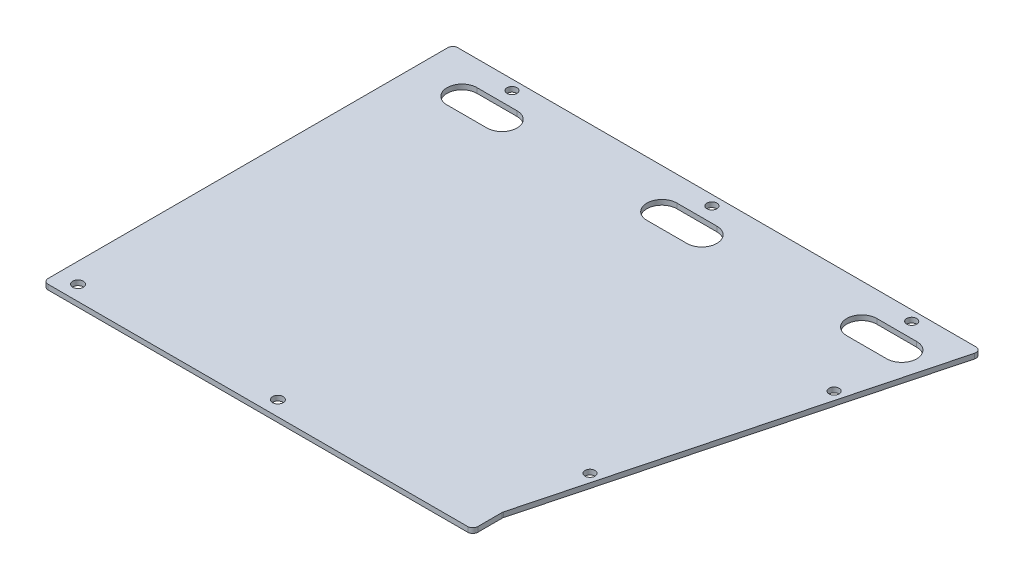
SolidWorks part; units mm, degrees
material "PC High Viscosity"
ref_plane "Front Plane" through (0, 0, 0) normal (0, 0, 1) x (1, 0, 0)
ref_plane "Top Plane" through (0, 0, 0) normal (0, 1, 0) x (1, 0, 0)
ref_plane "Right Plane" through (0, 0, 0) normal (1, 0, 0) x (0, 0, -1)
sketch "Sketch1" plane through (0, 0, 0) normal (0, 1, 0) x (1, 0, 0)
  line L0 (0, 0) -> (273.05, 0)
  line L1 (273.05, 0) -> (273.05, 19.05)
  line L2 (273.05, 19.05) -> (336.55, 260.35)
  line L3 (336.55, 260.35) -> (0, 260.35)
  line L4 (0, 260.35) -> (0, 0)
  dimension "D1" = 260.35
  dimension "D2" = 241.3
  dimension "D3" = 273.05
  dimension "D4" = 336.55
extrude "Boss-Extrude1" add sketch "Sketch1" along normal blind 3.175
fillet "Fillet1" radius 3.175 5 edges at (336.55, 1.5875, -260.35) (0, 1.5875, -260.35) (0, 1.5875, 0) (273.05, 1.5875, 0) (273.05, 1.5875, -19.05)
sketch "Sketch2" plane through (0, 3.175, 0) normal (0, 1, 0) x (1, 0, 0)
  line L0 (311.7215, 190.9534) -> (279.4009, 68.1349) construction
  line L1 (43.9782, 254) -> (297.9782, 254) construction
  line L2 (273.1545, 19.4472) -> (335.5018, 256.367) construction
  line L4 (298.1873, 139.5231) -> (304.3282, 137.9071) construction
  line L5 (332.4314, 260.35) -> (3.175, 260.35) construction
  point P0 (43.9782, 254)
  point P1 (170.9782, 254)
  point P2 (297.9782, 254)
  point P3 (279.4009, 68.1349)
  point P5 (311.7215, 190.9534)
  point P10 (167.8032, 260.35)
  point P15 (304.3282, 137.9071)
  dimension "D1" = 6.35
  dimension "D2" = 6.35
  dimension "D3" = 127
  dimension "D4" = 254
  dimension "D5" = 3.175
  dimension "D6" = 53.1812
hole_wizard "1/4 (0.25) Diameter Hole1" positions "Sketch3" profile "Sketch4" hole size "1/4" standard "ANSI Inch" end condition through all
sketch "Sketch3" plane through (0, 3.175, 0) normal (0, 1, 0) x (1, 0, 0)
  line L0 (43.9782, 254) -> (297.9782, 254) construction
  point P0 (43.9782, 254)
  point P3 (170.9782, 254)
  point P7 (297.9782, 254)
  point P10 (311.7215, 190.9534)
  point P17 (279.4009, 68.1349)
sketch "Sketch4" plane through (43.9782, 3.175, -254) normal (1, 0, 0) x (0, 0, 1)
  line L0 (0, 0) -> (0, 3.175)
  line L1 (0, 3.175) -> (3.175, 3.175)
  line L2 (3.175, 3.175) -> (3.175, 0)
  line L5 (3.175, 0) -> (0, 0)
  line L11 (0, -6.35) -> (0, 107.95) construction
  dimension "Thru Hole Dia." = 6.35
  dimension "Thru Hole Depth" = 3.175
sketch "Sketch5" plane through (0, 3.175, 0) normal (0, 1, 0) x (1, 0, 0)
  line L0 (0, 257.175) -> (0, 3.175) construction
  line L1 (3.175, 0) -> (269.875, 0) construction
  point P0 (12.7, 9.525)
  point P1 (139.7, 9.525)
  dimension "D1" = 127
  dimension "D2" = 12.7
  dimension "D3" = 9.525
hole_wizard "17/64 (0.26563) Diameter Hole1" positions "Sketch6" profile "Sketch7" hole size "17/64" standard "ANSI Inch" end condition through all
sketch "Sketch6" plane through (0, 3.175, 0) normal (0, 1, 0) x (1, 0, 0)
  point P0 (12.7, 9.525)
  point P3 (139.7, 9.525)
sketch "Sketch7" plane through (12.7, 3.175, -9.525) normal (1, 0, 0) x (0, 0, 1)
  line L0 (0, 0) -> (0, 3.175)
  line L1 (0, 3.175) -> (3.3735, 3.175)
  line L2 (3.3735, 3.175) -> (3.3735, 0)
  line L5 (3.3735, 0) -> (0, 0)
  line L11 (0, -6.35) -> (0, 107.95) construction
  dimension "Thru Hole Dia." = 6.747
  dimension "Thru Hole Depth" = 3.175
sketch "Sketch9" plane through (0, 3.175, 0) normal (0, 1, 0) x (1, 0, 0)
  line L0 (31.2782, 234.95) -> (56.6782, 234.95) construction
  line L1 (31.2782, 244.475) -> (56.6782, 244.475)
  line L2 (31.2782, 225.425) -> (56.6782, 225.425)
  line L3 (158.2782, 234.95) -> (183.6782, 234.95) construction
  line L4 (158.2782, 244.475) -> (183.6782, 244.475)
  line L5 (158.2782, 225.425) -> (183.6782, 225.425)
  line L6 (285.2782, 234.95) -> (310.6782, 234.95) construction
  line L7 (285.2782, 244.475) -> (310.6782, 244.475)
  line L8 (285.2782, 225.425) -> (310.6782, 225.425)
  circle A0 centre (297.9782, 254) radius 3.175 construction
  circle A1 centre (170.9782, 254) radius 3.175 construction
  circle A2 centre (43.9782, 254) radius 3.175 construction
  circle A3 centre (297.9782, 254) radius 3.175
  circle A4 centre (170.9782, 254) radius 3.175
  circle A5 centre (43.9782, 254) radius 3.175
  arc A6 (31.2782, 244.475) -> (31.2782, 225.425) centre (31.2782, 234.95) ccw
  arc A7 (56.6782, 225.425) -> (56.6782, 244.475) centre (56.6782, 234.95) ccw
  arc A8 (158.2782, 244.475) -> (158.2782, 225.425) centre (158.2782, 234.95) ccw
  arc A9 (183.6782, 225.425) -> (183.6782, 244.475) centre (183.6782, 234.95) ccw
  arc A10 (285.2782, 244.475) -> (285.2782, 225.425) centre (285.2782, 234.95) ccw
  arc A11 (310.6782, 225.425) -> (310.6782, 244.475) centre (310.6782, 234.95) ccw
  point P11 (43.9782, 234.95)
  point P17 (170.9782, 234.95)
  point P24 (297.9782, 234.95)
  point P30 (0, 0)
  point P31 (0, 0)
  point P32 (0, 0)
  dimension "D2" = 9.525
  dimension "D1" = 25.4
  dimension "D3" = 19.05
extrude "Cut-Extrude1" cut sketch "Sketch9" against normal through all
